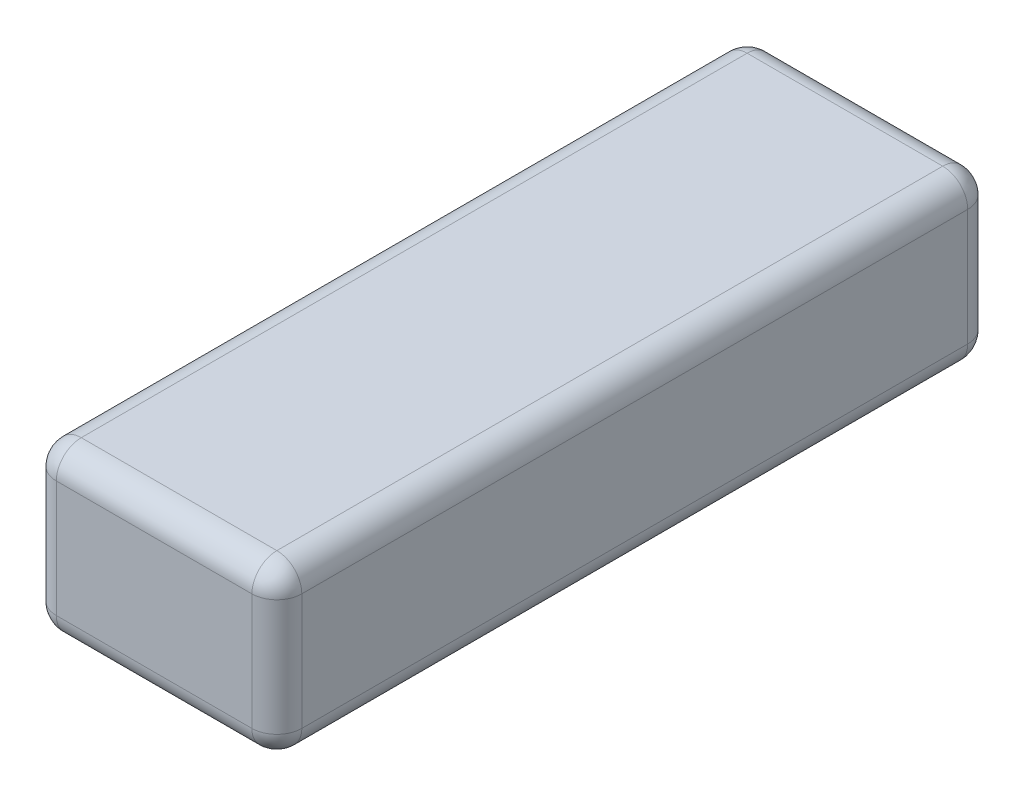
SolidWorks part; units mm, degrees
material "PLA"
ref_plane "Front Plane" through (0, 0, 0) normal (0, 0, 1) x (1, 0, 0)
ref_plane "Top Plane" through (0, 0, 0) normal (0, 1, 0) x (1, 0, 0)
ref_plane "Right Plane" through (0, 0, 0) normal (1, 0, 0) x (0, 0, -1)
sketch "Sketch1" plane through (0, 0, 0) normal (0, 1, 0) x (1, 0, 0)
  line L1 (-14.75, -43) -> (14.75, -43)
  line L2 (-14.75, -43) -> (-14.75, 43)
  line L3 (-14.75, 43) -> (14.75, 43)
  line L4 (14.75, -43) -> (14.75, 43)
  line L5 (-14.75, -43) -> (14.75, 43) construction
  line L6 (-14.75, 43) -> (14.75, -43) construction
  point P0 (0, 0)
  dimension "D1" = 86
  dimension "D2" = 29.5
extrude "Boss-Extrude1" add sketch "Sketch1" along normal mid plane 20
fillet "Fillet1" radius 3 12 edges at (14.75, 10, 0) (14.75, 0, -43) (14.75, -10, 0) (0, -10, -43) (0, 10, -43) (-14.75, 0, -43) (-14.75, -10, 0) (-14.75, 10, 0) (-14.75, 0, 43) (0, -10, 43) (0, 10, 43) (14.75, 0, 43)
